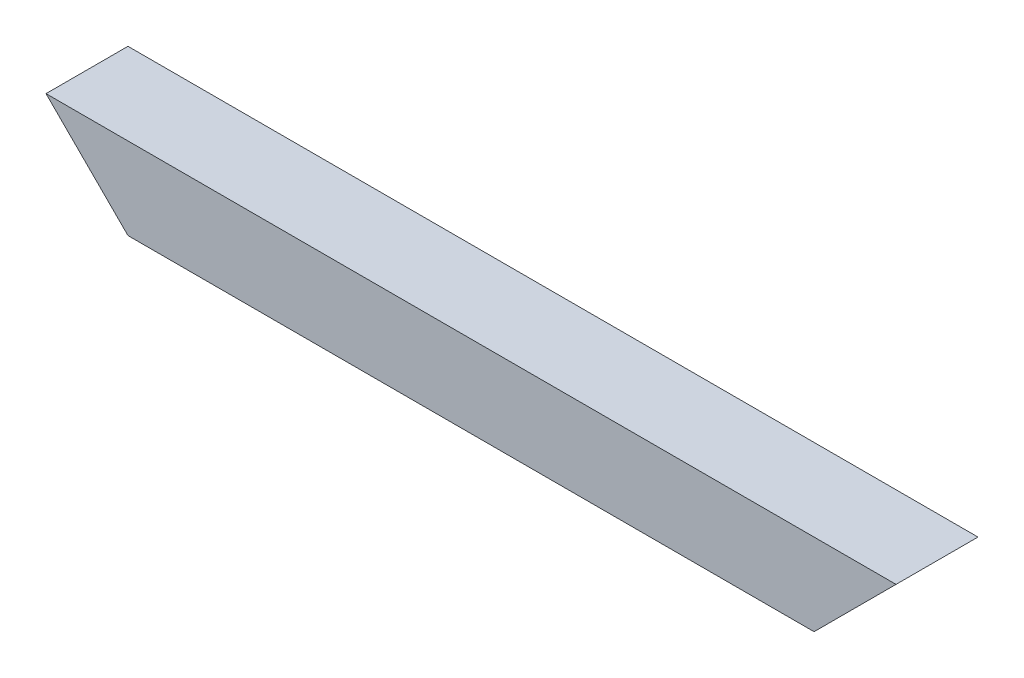
SolidWorks part; units mm, degrees
ref_plane "Front Plane" through (0, 0, 0) normal (0, 0, 1) x (1, 0, 0)
ref_plane "Top Plane" through (0, 0, 0) normal (0, 1, 0) x (1, 0, 0)
ref_plane "Right Plane" through (0, 0, 0) normal (1, 0, 0) x (0, 0, -1)
sketch "Sketch1" plane through (0, 0, 0) normal (1, 0, 0) x (0, 0, -1)
  line L1 (0, 0) -> (38.1, 0)
  line L2 (0, 0) -> (0, -38.1)
  line L3 (0, -38.1) -> (38.1, -38.1)
  line L4 (38.1, 0) -> (38.1, -38.1)
  dimension "D1" = 38.1
  dimension "D2" = 38.1
extrude "Boss-Extrude1" add sketch "Sketch1" along normal blind 395.1313
sketch "Sketch2" plane through (0, 0, 0) normal (0, 0, 1) x (1, 0, 0)
  line L0 (0, -38.1) -> (38.1, -38.1)
  line L1 (395.1313, -38.1) -> (0, -38.1) construction
  line L2 (38.1, -38.1) -> (0, 0)
  dimension "D1" = 38.1
extrude "Cut-Extrude1" cut sketch "Sketch2" against normal through all and the other way through all contours L0 L2
sketch "Sketch3" plane through (0, 0, 0) normal (0, 0, 1) x (1, 0, 0)
  line L0 (395.1313, -38.1) -> (357.0313, -38.1)
  line L1 (395.1313, -38.1) -> (38.1, -38.1) construction
  line L2 (357.0313, -38.1) -> (395.1313, 0)
  dimension "D1" = 38.1
extrude "Cut-Extrude2" cut sketch "Sketch3" against normal through all and the other way through all flip side to cut contours L0 L2
